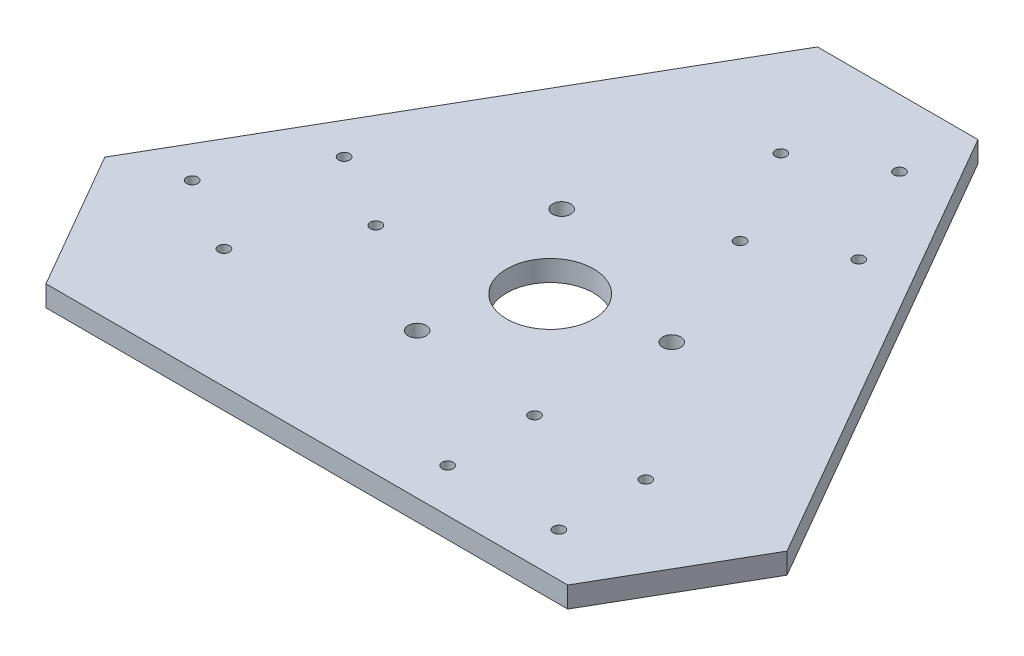
SolidWorks part; units mm, degrees
ref_plane "前视基准面" through (0, 0, 0) normal (0, 0, 1) x (1, 0, 0)
ref_plane "上视基准面" through (0, 0, 0) normal (0, 1, 0) x (1, 0, 0)
ref_plane "右视基准面" through (0, 0, 0) normal (1, 0, 0) x (0, 0, -1)
sketch "草图1" plane through (0, 0, 0) normal (0, 1, 0) x (1, 0, 0)
  line L1 (115.4701, 0) -> (57.735, 100)
  line L2 (57.735, 100) -> (-57.735, 100)
  line L3 (-57.735, 100) -> (-115.4701, 0)
  line L4 (-115.4701, 0) -> (-57.735, -100)
  line L5 (-57.735, -100) -> (57.735, -100)
  line L6 (57.735, -100) -> (115.4701, 0)
  circle A0 centre (0, 0) radius 100 construction
  dimension "D1" = 200
extrude "凸台-拉伸1" add sketch "草图1" along normal blind 6
sketch "草图2" plane through (0, 6, 0) normal (0, 1, 0) x (1, 0, 0)
  line L1 (-20, -20) -> (20, -20) construction
  line L2 (-20, -20) -> (-20, 20) construction
  line L3 (-20, 20) -> (20, 20) construction
  line L4 (20, -20) -> (20, 20) construction
  line L5 (-20, -20) -> (20, 20) construction
  line L6 (-20, 20) -> (20, -20) construction
  circle A0 centre (20, 20) radius 2.5 construction
  circle A1 centre (20, -20) radius 2.5 construction
  circle A2 centre (-20, -20) radius 2.5 construction
  circle A3 centre (-20, 20) radius 2.5 construction
  circle A4 centre (0, 0) radius 12.5
  point P0 (0, 0)
  dimension "D3" = 5
  dimension "D4" = 5
  dimension "D5" = 5
  dimension "D6" = 5
  dimension "D7" = 25
  dimension "D1" = 40
  dimension "D2" = 40
extrude "切除-拉伸1" cut sketch "草图2" against normal through all
sketch "草图3" plane through (0, 6, 0) normal (0, 1, 0) x (1, 0, 0)
  line L0 (-23.094, 100) -> (-98.1495, -30)
  line L1 (57.735, 100) -> (-57.735, 100) construction
  line L2 (-115.4701, 0) -> (-57.735, -100) construction
  line L3 (98.1495, -30) -> (23.094, 100)
  line L4 (-75.0555, -70) -> (75.0555, -70)
  line L5 (-57.735, 100) -> (-115.4701, 0) construction
  line L6 (-23.094, 100) -> (-57.735, 100)
  line L7 (-57.735, 100) -> (-115.4701, 0)
  line L8 (-115.4701, 0) -> (-98.1495, -30)
  line L9 (-75.0555, -70) -> (-57.735, -100)
  line L10 (-57.735, -100) -> (57.735, -100)
  line L11 (57.735, -100) -> (75.0555, -70)
  line L12 (98.1495, -30) -> (115.4701, 0)
  line L13 (115.4701, 0) -> (57.735, 100)
  line L14 (57.735, 100) -> (23.094, 100)
  point P13 (0, 0)
  dimension "D2" = 30
  dimension "D1" = 3
extrude "切除-拉伸2" cut sketch "草图3" against normal through all
sketch "草图4" plane through (0, 6, 0) normal (0, 1, 0) x (1, 0, 0)
  line L0 (0, 0) -> (0, 100) construction
  line L1 (23.094, 100) -> (-23.094, 100) construction
  circle A0 centre (0, 85) radius 2.5
  circle A3 centre (73.6122, -42.5) radius 2.5
  circle A4 centre (-73.6122, -42.5) radius 2.5
  point P13 (0, 0)
  dimension "D1" = 5
  dimension "D2" = 15
  dimension "D3" = 3
extrude "切除-拉伸3" [suppressed] cut sketch "草图4" against normal through all
sketch "草图6" plane through (0, 6, 0) normal (0, 1, 0) x (1, 0, 0)
  line L0 (0, 0) -> (-10, -28.2843) construction
  line L3 (0, 0) -> (0, -70) construction
  line L4 (75.0555, -70) -> (-75.0555, -70) construction
  circle A0 centre (-10, -28.2843) radius 2.6
  circle A1 centre (-19.4949, 22.8024) radius 2.6
  circle A2 centre (29.4949, 5.4819) radius 2.6
  point P12 (0, 0)
  dimension "D3" = 5.2
  dimension "D1" = 30
  dimension "D2" = 10
  dimension "D4" = 3
extrude "切除-拉伸5" cut sketch "草图6" against normal through all
sketch "草图7" plane through (0, 0, 0) normal (0, 1, 0) x (1, 0, 0)
  line L0 (0, 0) -> (0, -70) construction
  line L1 (75.0555, -70) -> (-75.0555, -70) construction
  line L2 (0, -45) -> (77.1484, -45) construction
  line L13 (60, -57.5) -> (28, -57.5) construction
  line L14 (60, -57.5) -> (60, -32.5) construction
  line L15 (60, -32.5) -> (28, -32.5) construction
  line L16 (28, -57.5) -> (28, -32.5) construction
  line L17 (60, -57.5) -> (28, -32.5) construction
  line L18 (60, -32.5) -> (28, -57.5) construction
  circle A4 centre (60, -32.5) radius 1.6
  circle A5 centre (28, -32.5) radius 1.6
  circle A6 centre (60, -57.5) radius 1.6
  circle A7 centre (28, -57.5) radius 1.6
  circle A8 centre (-58.1458, -35.7115) radius 1.6
  circle A9 centre (-42.1458, -7.9987) radius 1.6
  circle A10 centre (-79.7965, -23.2115) radius 1.6
  circle A11 centre (-63.7965, 4.5013) radius 1.6
  circle A12 centre (-1.8542, 68.2115) radius 1.6
  circle A13 centre (14.1458, 40.4987) radius 1.6
  circle A14 centre (19.7965, 80.7115) radius 1.6
  circle A15 centre (35.7965, 52.9987) radius 1.6
  point P7 (44, -45)
  point P35 (0, 0)
  dimension "D4" = 44
  dimension "D5" = 3.2
  dimension "D6" = 3.2
  dimension "D7" = 3.2
  dimension "D8" = 3.2
  dimension "D1" = 25
  dimension "D2" = 32
  dimension "D3" = 25
  dimension "D9" = 3
extrude "切除-拉伸8" cut sketch "草图7" along normal through all
